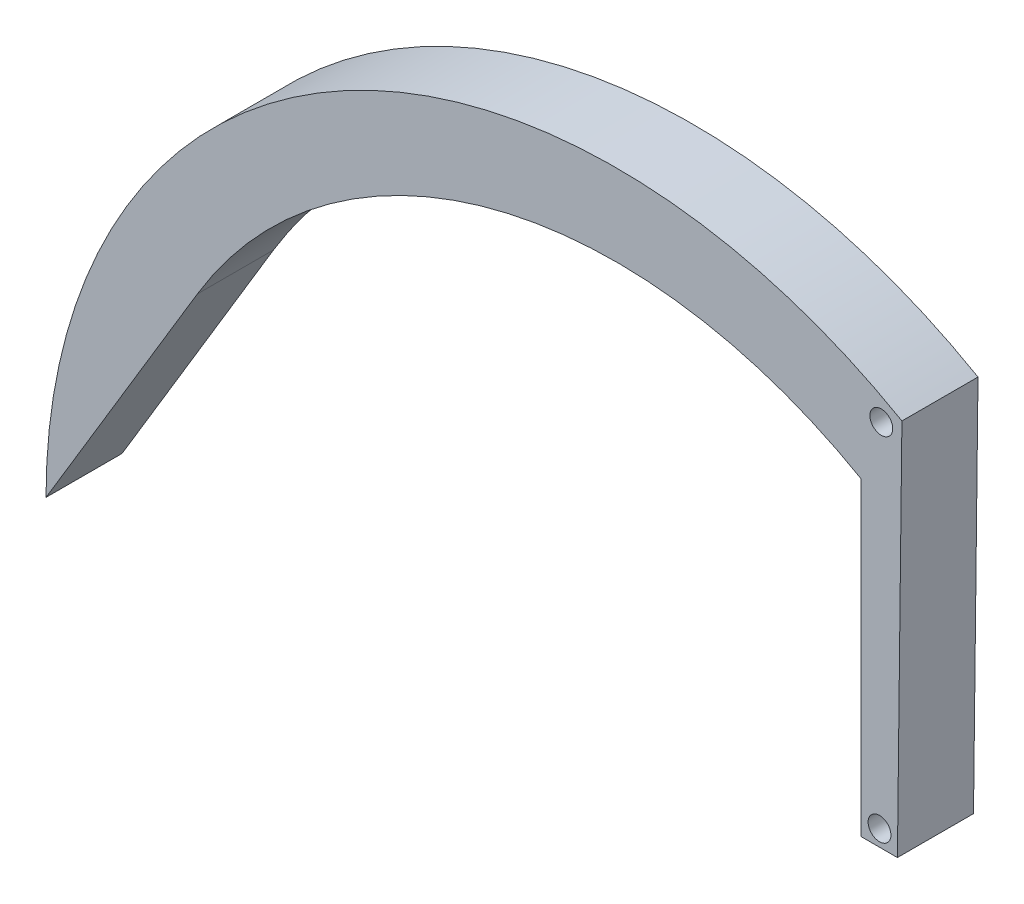
SolidWorks part; units mm, degrees
ref_plane "前视基准面" through (0, 0, 0) normal (0, 0, 1) x (1, 0, 0)
ref_plane "上视基准面" through (0, 0, 0) normal (0, 1, 0) x (1, 0, 0)
ref_plane "右视基准面" through (0, 0, 0) normal (1, 0, 0) x (0, 0, -1)
other "Configuration Table"
sketch "草图9" plane through (0, 0, 0) normal (0, 0, 1) x (1, 0, 0)
  line L0 (55, 0) -> (-55, 0) construction
  line L1 (-150, 0) -> (-110.2034, 66.2248)
  line L2 (64.2855, 111.3458) -> (64.2855, 29.9108)
  line L3 (75, 129.9038) -> (73.8177, 29.9108)
  line L4 (73.8177, 29.9108) -> (64.2855, 29.9108)
  arc A0 (-110.2034, 66.2248) -> (64.2855, 111.3458) centre (0, 0) cw
  arc A1 (-150, 0) -> (75, 129.9038) centre (0, 0) cw
extrude "凸台-拉伸2" add sketch "草图9" along normal blind 20
sketch "草图10" plane through (0, 0, 20) normal (0, 0, 1) x (1, 0, 0)
  circle A0 centre (69.5887, 126.9287) radius 3
extrude "切除-拉伸1" cut sketch "草图10" against normal through all
sketch "草图11" plane through (0, 0, 20) normal (0, 0, 1) x (1, 0, 0)
  circle A0 centre (69.1144, 34.1626) radius 3
extrude "切除-拉伸2" cut sketch "草图11" against normal through all
